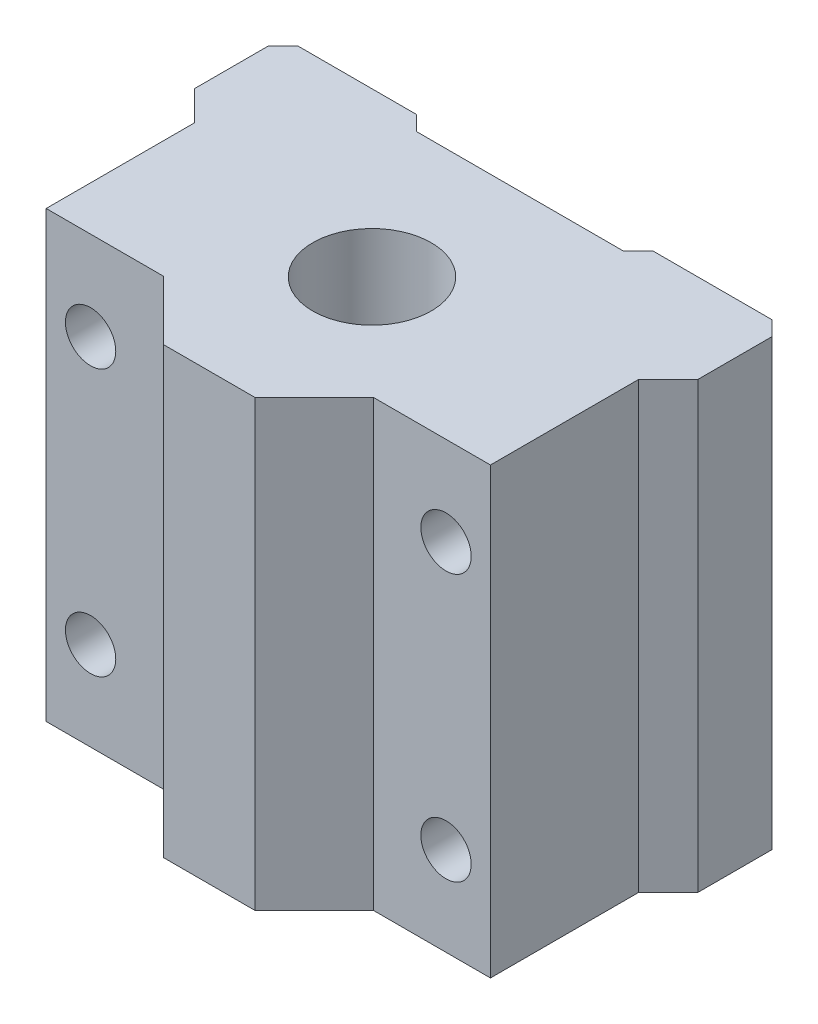
SolidWorks part; units mm, degrees
ref_plane "Front Plane" through (0, 0, 0) normal (0, 0, 1) x (1, 0, 0)
ref_plane "Top Plane" through (0, 0, 0) normal (0, 1, 0) x (1, 0, 0)
ref_plane "Right Plane" through (0, 0, 0) normal (1, 0, 0) x (0, 0, -1)
sketch "Sketch1" plane through (0, 0, 0) normal (0, 1, 0) x (1, 0, 0)
  line L0 (0, 0) -> (-15.6142, 0) construction
  line L1 (0, 0) -> (0, -2.9646) construction
  line L2 (-7, 10) -> (7, 10)
  line L3 (17, 10) -> (17, 5)
  line L4 (17, 5) -> (15, 3)
  line L5 (15, 3) -> (15, -7)
  line L6 (15, -7) -> (7.0913, -7)
  line L7 (7.0913, -7) -> (3.0913, -11)
  line L8 (3.0913, -11) -> (-3.0913, -11)
  line L9 (7, 10) -> (8, 11)
  line L10 (8, 11) -> (16, 11)
  line L11 (16, 11) -> (17, 10)
  line L12 (-7, 10) -> (-8, 11)
  line L13 (-8, 11) -> (-16, 11)
  line L14 (-16, 11) -> (-17, 10)
  line L15 (-17, 10) -> (-17, 5)
  line L16 (-17, 5) -> (-15, 3)
  line L17 (-15, 3) -> (-15, -7)
  line L18 (-7.0913, -7) -> (-3.0913, -11)
  line L19 (-15, -7) -> (-7.0913, -7)
  circle A0 centre (0, 0) radius 4
  point P5 (0, 10)
  point P26 (0, -11)
  dimension "D1" = 8
  dimension "D2" = 17
  dimension "D3" = 45
  dimension "D4" = 45
  dimension "D5" = 11
  dimension "D6" = 6
  dimension "D7" = 7
  dimension "D8" = 22
  dimension "D9" = 135
  dimension "D10" = 8
  dimension "D11" = 135
  dimension "D12" = 8
  dimension "D13" = 1
extrude "Boss-Extrude1" add sketch "Sketch1" along normal blind 30
sketch "Sketch2" plane through (0, 0, 7) normal (0, 0, 1) x (1, 0, 0)
  line L1 (0, 0) -> (0, 30) construction
  line L2 (-3.0913, 30) -> (3.0913, 30) construction
  line L3 (-3.0913, 0) -> (3.0913, 0) construction
  line L4 (-3.0913, 0) -> (3.0913, 0) construction
  line L5 (0, 15) -> (-9.1619, 15) construction
  circle A0 centre (12, 24) radius 1.7
  circle A1 centre (-12, 24) radius 1.7
  circle A2 centre (-12, 6) radius 1.7
  circle A3 centre (12, 6) radius 1.7
  point P4 (0, 15)
  point P10 (0, 30)
  point P11 (0, 0)
  dimension "D1" = 3.4
  dimension "D2" = 12
  dimension "D3" = 9
extrude "Cut-Extrude1" cut sketch "Sketch2" against normal up to surface (18 mm away) up to face at (-12, 15, -11)
